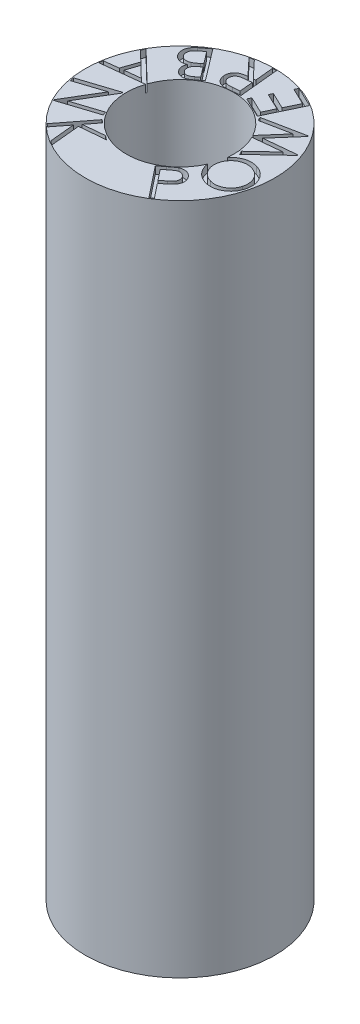
SolidWorks part; units mm, degrees
ref_plane "Front Plane" through (0, 0, 0) normal (0, 0, 1) x (1, 0, 0)
ref_plane "Top Plane" through (0, 0, 0) normal (0, 1, 0) x (1, 0, 0)
ref_plane "Right Plane" through (0, 0, 0) normal (1, 0, 0) x (0, 0, -1)
sketch "Sketch1" plane through (0, 0, 0) normal (0, 1, 0) x (1, 0, 0)
  circle A0 centre (0, 0) radius 2.15
  circle A1 centre (0, 0) radius 3.8
  dimension "D1" = 4.3
  dimension "D2" = 7.6
extrude "Boss-Extrude1" add sketch "Sketch1" along normal blind 27
sketch "Sketch2" plane through (0, 27, 0) normal (0, 1, 0) x (1, 0, 0)
  text T0 "POWERBANK" font "Century Gothic" height in points 6
extrude "Cut-Extrude1" cut sketch "Sketch2" against normal blind 0.3
